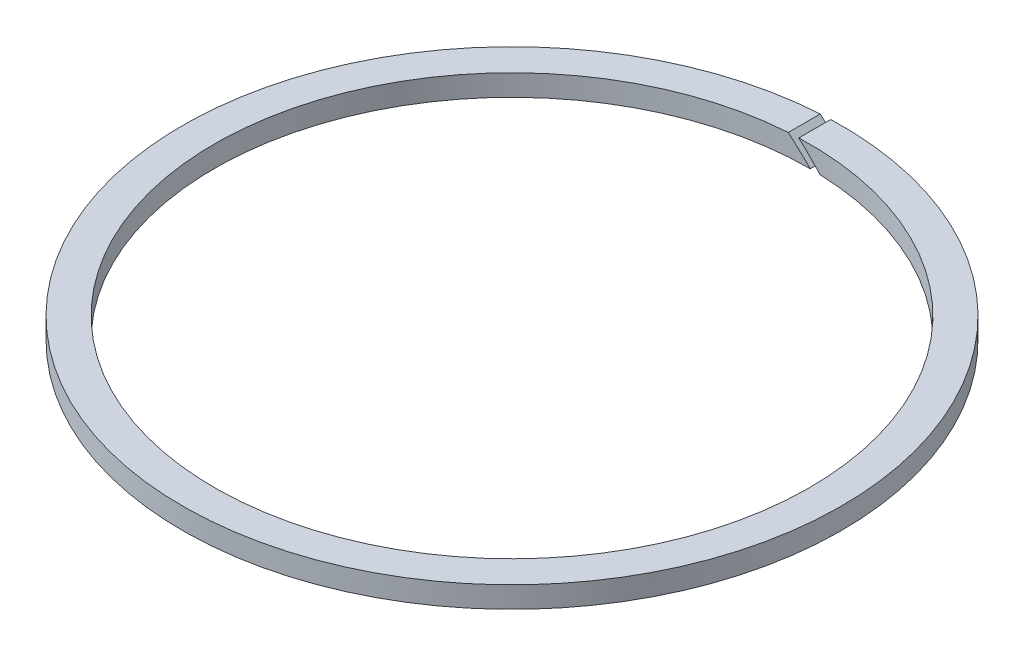
SolidWorks part; units mm, degrees
ref_plane "Front Plane" through (0, 0, 0) normal (0, 0, 1) x (1, 0, 0)
ref_plane "Top Plane" through (0, 0, 0) normal (0, 1, 0) x (1, 0, 0)
ref_plane "Right Plane" through (0, 0, 0) normal (1, 0, 0) x (0, 0, -1)
sketch "Sketch1" plane through (0, 0, 0) normal (0, 1, 0) x (1, 0, 0)
  circle A0 centre (0, 0) radius 46.5
  circle A1 centre (0, 0) radius 42
  dimension "D1" = 93
  dimension "D2" = 84
extrude "Boss-Extrude1" add sketch "Sketch1" along normal mid plane 3
sketch "Sketch2" plane through (0, 0, 0) normal (0, 0, 1) x (1, 0, 0)
  line L0 (46.5, -1.5) -> (46.5, 1.5) construction
  line L1 (46.5, 1.5) -> (-46.5, 1.5) construction
  line L2 (-46.5, 1.5) -> (-46.5, -1.5) construction
  line L3 (-46.5, -1.5) -> (46.5, -1.5) construction
  line L4 (42, 1.5) -> (-42, 1.5) construction
  line L5 (46.5, -1.5) -> (46.5, 1.5)
  line L6 (46.5, 1.5) -> (-46.5, 1.5)
  line L7 (-46.5, 1.5) -> (-46.5, -1.5)
  line L8 (-46.5, -1.5) -> (46.5, -1.5)
  line L9 (42, 1.5) -> (-42, 1.5)
  line L10 (-1.5, 1.5) -> (1.5, -1.5)
  line L11 (-2.9142, 1.5) -> (0.0858, -1.5)
  point P6 (0, 0)
  dimension "D1" = 135
  dimension "D2" = 1
extrude "Cut-Extrude1" cut sketch "Sketch2" against normal through all contours L9 L11 L8 L10
